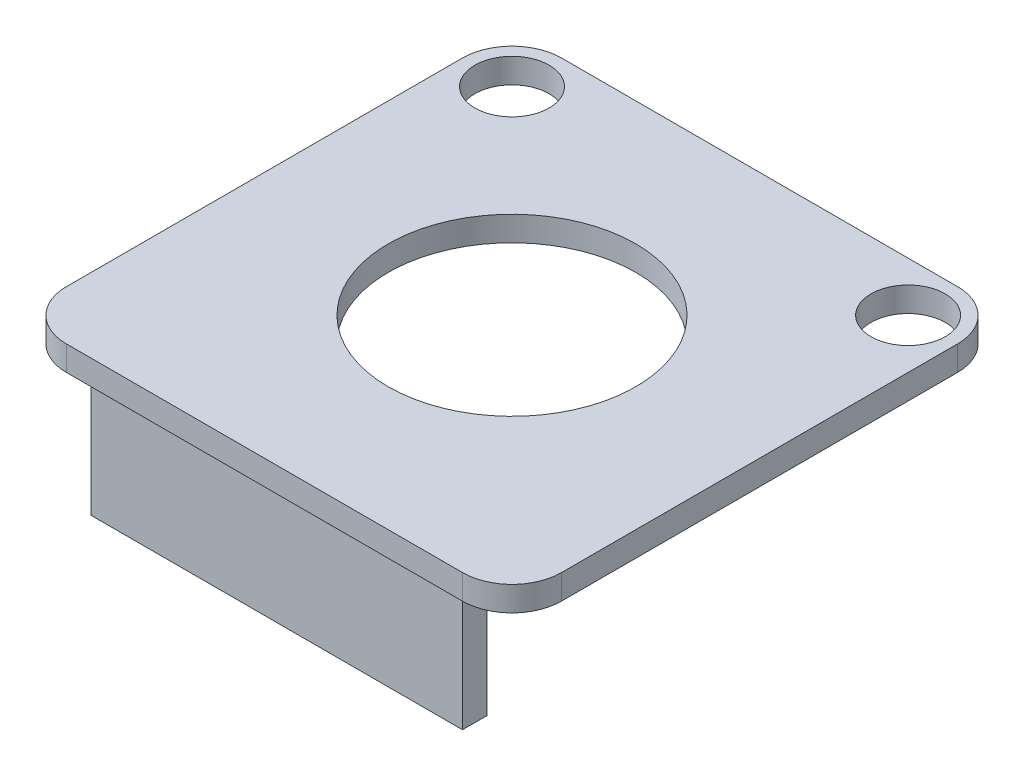
SolidWorks part; units mm, degrees
ref_plane "Front Plane" through (0, 0, 0) normal (0, 0, 1) x (1, 0, 0)
ref_plane "Top Plane" through (0, 0, 0) normal (0, 1, 0) x (1, 0, 0)
ref_plane "Right Plane" through (0, 0, 0) normal (1, 0, 0) x (0, 0, -1)
sketch "Sketch2" plane through (0, 0, 0) normal (0, 1, 0) x (1, 0, 0)
  line L1 (-10, -10) -> (10, -10)
  line L2 (-10, -10) -> (-10, 10)
  line L3 (-10, 10) -> (10, 10)
  line L4 (10, -10) -> (10, 10)
  line L5 (-10, -10) -> (10, 10) construction
  line L6 (-10, 10) -> (10, -10) construction
  point P0 (0, 0)
  dimension "D1" = 20
  dimension "D2" = 20
extrude "Boss-Extrude1" add sketch "Sketch2" along normal blind 1
sketch "Sketch3" plane through (0, 1, 0) normal (0, 1, 0) x (1, 0, 0)
  line L0 (-10, 10) -> (-10, -10) construction
  line L1 (10, 10) -> (-10, 10) construction
  line L2 (10, -10) -> (10, 10) construction
  circle A0 centre (0, 0) radius 5
  circle A1 centre (-8, 8) radius 1.5
  circle A2 centre (8, 8) radius 1.5
  point P7 (2.6561, 8.4928)
  point P8 (-7.216, 7.9)
  dimension "D1" = 10
  dimension "D2" = 3
  dimension "D3" = 2
  dimension "D4" = 2
  dimension "D5" = 2
extrude "Cut-Extrude1" cut sketch "Sketch3" against normal through all
fillet "Fillet1" radius 2 4 edges at (10, 0.5, 10) (10, 0.5, -10) (-10, 0.5, 10) (-10, 0.5, -10)
sketch "Sketch4" plane through (0, 0, 0) normal (0, -1, 0) x (1, 0, 0)
  line L0 (-8, 10) -> (8, 10) construction
  line L1 (-7.5, 9.5) -> (7.5, 9.5)
  line L2 (-7.5, 9.5) -> (-7.5, 8.5)
  line L3 (-7.5, 8.5) -> (7.5, 8.5)
  line L4 (7.5, 9.5) -> (7.5, 8.5)
  line L5 (-7.5, 9.5) -> (7.5, 8.5) construction
  line L6 (-7.5, 8.5) -> (7.5, 9.5) construction
  point P0 (0, 9)
  point P5 (0, 0)
  dimension "D1" = 1
  dimension "D2" = 15
  dimension "D3" = 0.5
extrude "Boss-Extrude2" add sketch "Sketch4" along normal blind 5
